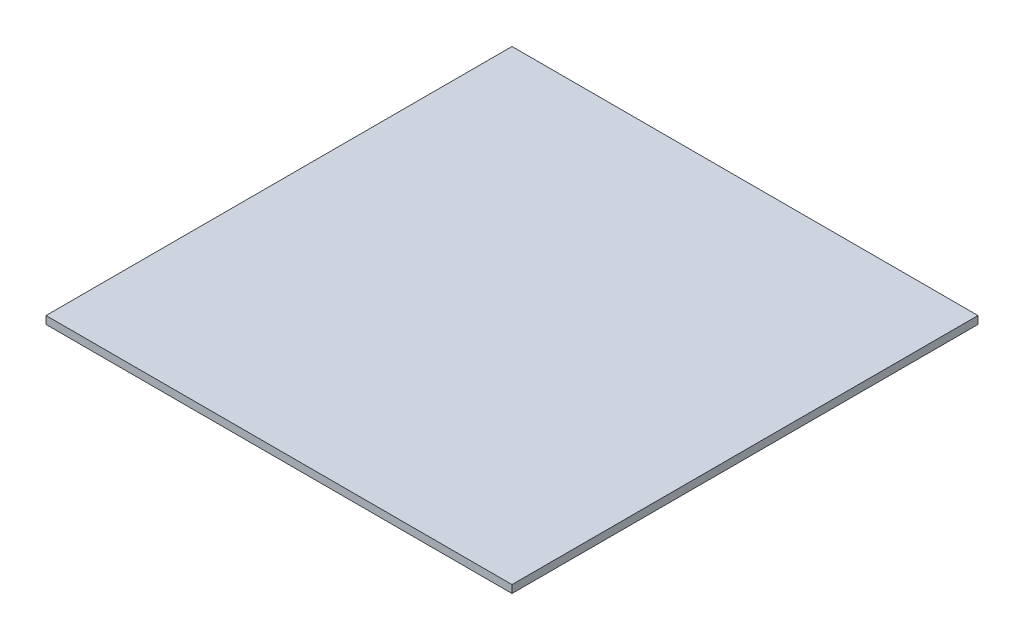
SolidWorks part; units mm, degrees
ref_plane "Front Plane" through (0, 0, 0) normal (0, 0, 1) x (1, 0, 0)
ref_plane "Top Plane" through (0, 0, 0) normal (0, 1, 0) x (1, 0, 0)
ref_plane "Right Plane" through (0, 0, 0) normal (1, 0, 0) x (0, 0, -1)
sketch "Sketch2" plane through (0, 0, 0) normal (0, 1, 0) x (1, 0, 0)
  line L1 (9, 9) -> (-9, 9)
  line L2 (9, 9) -> (9, -9)
  line L3 (9, -9) -> (-9, -9)
  line L4 (-9, 9) -> (-9, -9)
  line L5 (9, 9) -> (-9, -9) construction
  line L6 (9, -9) -> (-9, 9) construction
  point P0 (0, 0)
  dimension "D1" = 18
  dimension "D2" = 18
extrude "Boss-Extrude1" add sketch "Sketch2" along normal blind 0.3
